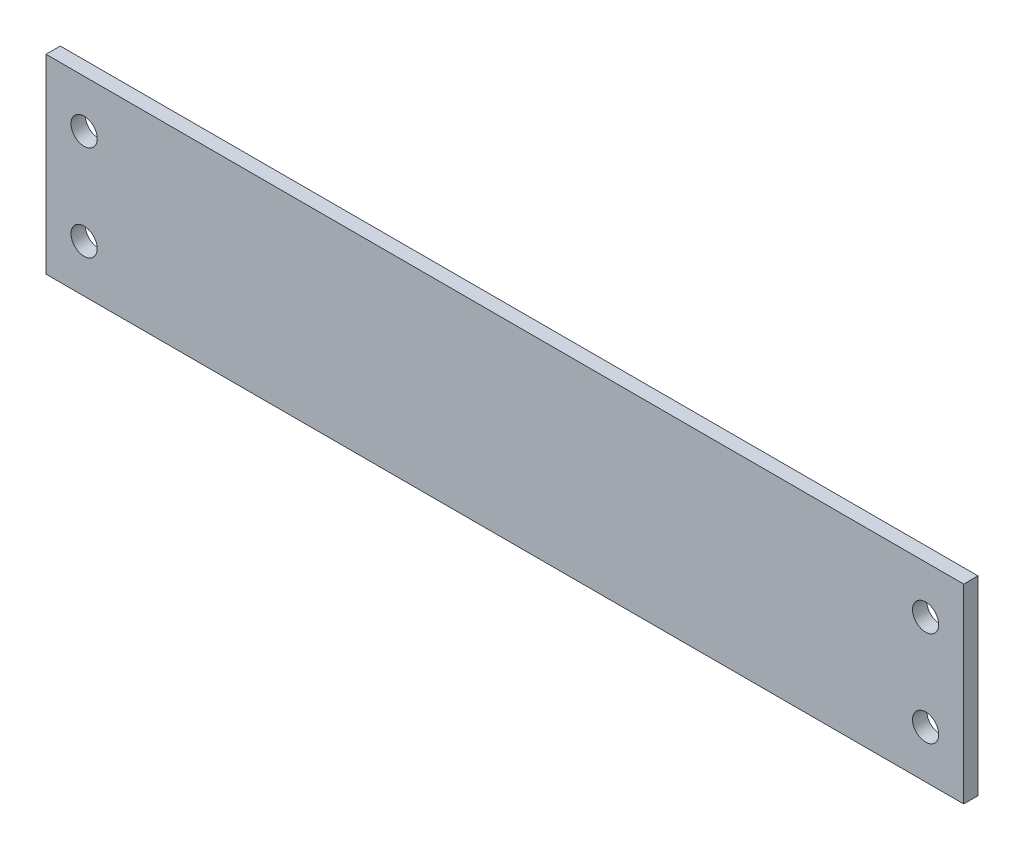
SolidWorks part; units mm, degrees
ref_plane "Front Plane" through (0, 0, 0) normal (0, 0, 1) x (1, 0, 0)
ref_plane "Top Plane" through (0, 0, 0) normal (0, 1, 0) x (1, 0, 0)
ref_plane "Right Plane" through (0, 0, 0) normal (1, 0, 0) x (0, 0, -1)
sketch "Extrusion Base Sketch" plane through (0, 0, 0) normal (0, 0, 1) x (1, 0, 0)
  line L0 (0, 40) -> (0, 0)
  line L5 (-192.75, 40) -> (0, 40)
  line L6 (-170.75, 40) -> (-170.75, 0) construction
  line L7 (-192.75, 0) -> (0, 0)
  line L8 (-22, 40) -> (-22, 0) construction
  line L9 (-192.75, 40) -> (-192.75, 0)
  line L10 (-8, 30) -> (-8, 10) construction
  line L11 (-8, 20) -> (0, 20) construction
  line L12 (-184.75, 30) -> (-184.75, 10) construction
  point P0 (14.0278, 16.0461)
  dimension "D3" = 40
  dimension "D1" = 148.75
  dimension "D2" = 20
extrude "Extrusion Base Extrude" add sketch "Extrusion Base Sketch" along normal blind 3
hole_wizard "M5 Mounting Holes" positions "M5 Mounting Holes Position Sketch" profile "M5 Mounting Holes Profile Sketch" hole size "M5" standard "ANSI Metric" end condition through all
sketch "M5 Mounting Holes Position Sketch" plane through (0, 0, 3) normal (0, 0, 1) x (1, 0, 0)
  point P0 (-8, 30)
  point P2 (-8, 10)
  point P4 (-184.75, 30)
  point P6 (-184.75, 10)
sketch "M5 Mounting Holes Profile Sketch" plane through (-8, 30, 3) normal (1, 0, 0) x (0, -1, 0)
  line L0 (0, 0) -> (0, 3)
  line L1 (0, 3) -> (2.75, 3)
  line L2 (2.75, 3) -> (2.75, 0)
  line L5 (2.75, 0) -> (0, 0)
  line L11 (0, -6.35) -> (0, 107.95) construction
  dimension "Thru Hole Dia." = 5.5
  dimension "Thru Hole Depth" = 3
equation "\"Total Height\"= 40mm"
equation "\"Logo Length\" = 148.75"
equation "\"D3@Extrusion Base Sketch\" = \"Total Height\""
equation "\"D1@Extrusion Base Sketch\"=\"Logo Length\""
